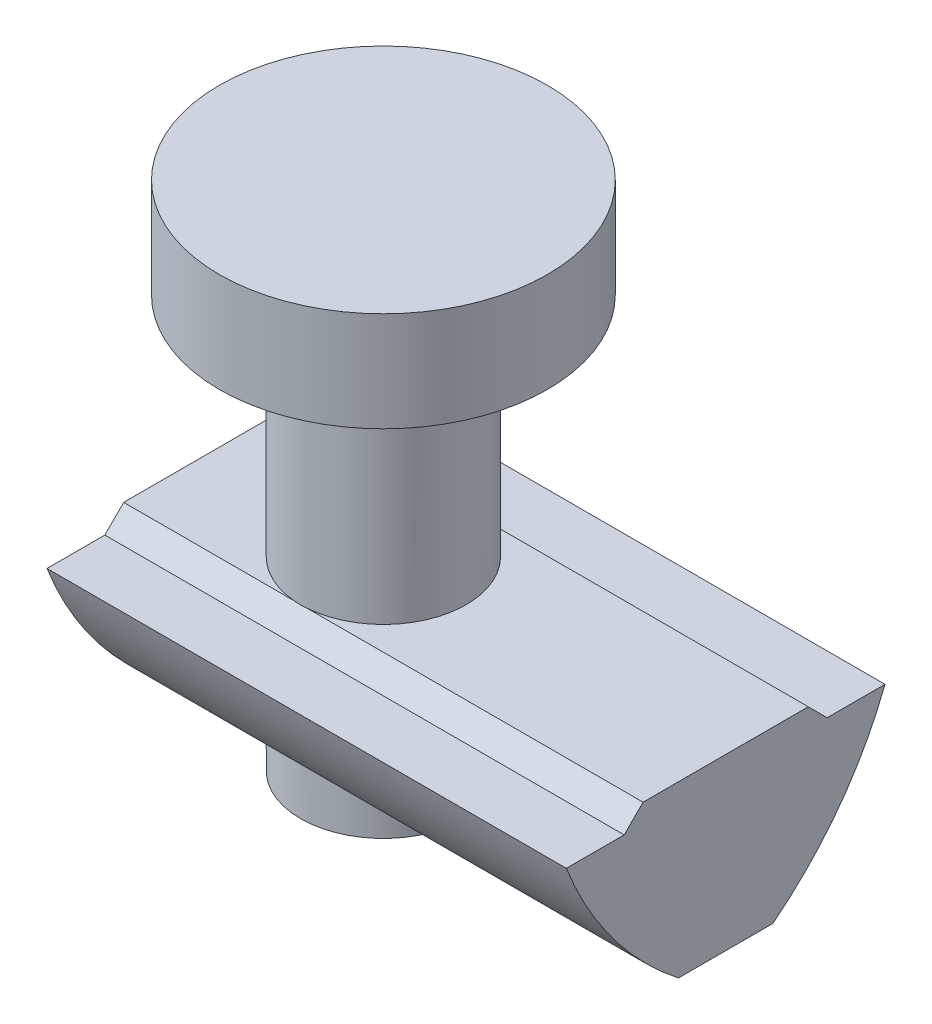
SolidWorks part; units mm, degrees
ref_plane "Front Plane" through (0, 0, 0) normal (0, 0, 1) x (1, 0, 0)
ref_plane "Top Plane" through (0, 0, 0) normal (0, 1, 0) x (1, 0, 0)
ref_plane "Right Plane" through (0, 0, 0) normal (1, 0, 0) x (0, 0, -1)
sketch "Sketch1" plane through (0, 0, 0) normal (0, 1, 0) x (1, 0, 0)
  circle A0 centre (0, 0) radius 6.9469
  dimension "D1" = 13.8938
extrude "Boss-Extrude1" add sketch "Sketch1" along normal blind 4.22
sketch "Sketch2" plane through (0, 0, 0) normal (0, -1, 0) x (-1, 0, 0)
  circle A0 centre (0, 0) radius 3.51
  dimension "D1" = 7.02
extrude "Boss-Extrude2" add sketch "Sketch2" along normal blind 17.46 contours A0
sketch "Sketch3" plane through (0, 0, 0) normal (1, 0, 0) x (0, 0, -1)
  line L0 (-6.25, -10.41) -> (-6.75, -10.41)
  line L1 (6.75, -9.61) -> (6.75, -16.81) construction
  line L2 (6.75, -16.81) -> (-6.75, -16.81) construction
  line L3 (-6.75, -9.61) -> (6.75, -9.61) construction
  line L4 (0, 0) -> (0, -9.61) construction
  line L5 (-6.75, -16.81) -> (-6.75, -9.61) construction
  line L6 (-2, -16.81) -> (2, -16.81)
  line L7 (-6.25, -10.41) -> (-4.3, -10.41)
  line L8 (-3.5, -9.61) -> (3.5, -9.61)
  line L9 (6.25, -10.41) -> (4.3, -10.41)
  line L10 (0, -9.61) -> (0, -16.81) construction
  line L12 (-3.5, -9.61) -> (-4.3, -10.41)
  line L13 (3.5, -9.61) -> (4.3, -10.41)
  line L14 (6.25, -10.41) -> (6.75, -10.41)
  arc A0 (-6.75, -10.41) -> (-2, -16.81) centre (7.2372, -4.9916) ccw
  arc A3 (6.75, -10.41) -> (2, -16.81) centre (-7.2372, -4.9916) cw
  point P0 (-6.75, -10.4862)
  point P19 (3.9, -9.61)
  point P25 (-3.9, -9.61)
  dimension "D6" = 15
  dimension "D1" = 7.2
  dimension "D2" = 13.5
  dimension "D3" = 9.61
  dimension "D5" = 4
  dimension "D7" = 0.8
  dimension "D8" = 7.8
extrude "Boss-Extrude3" add sketch "Sketch3" along normal blind 14.5 and the other way blind 7.5
